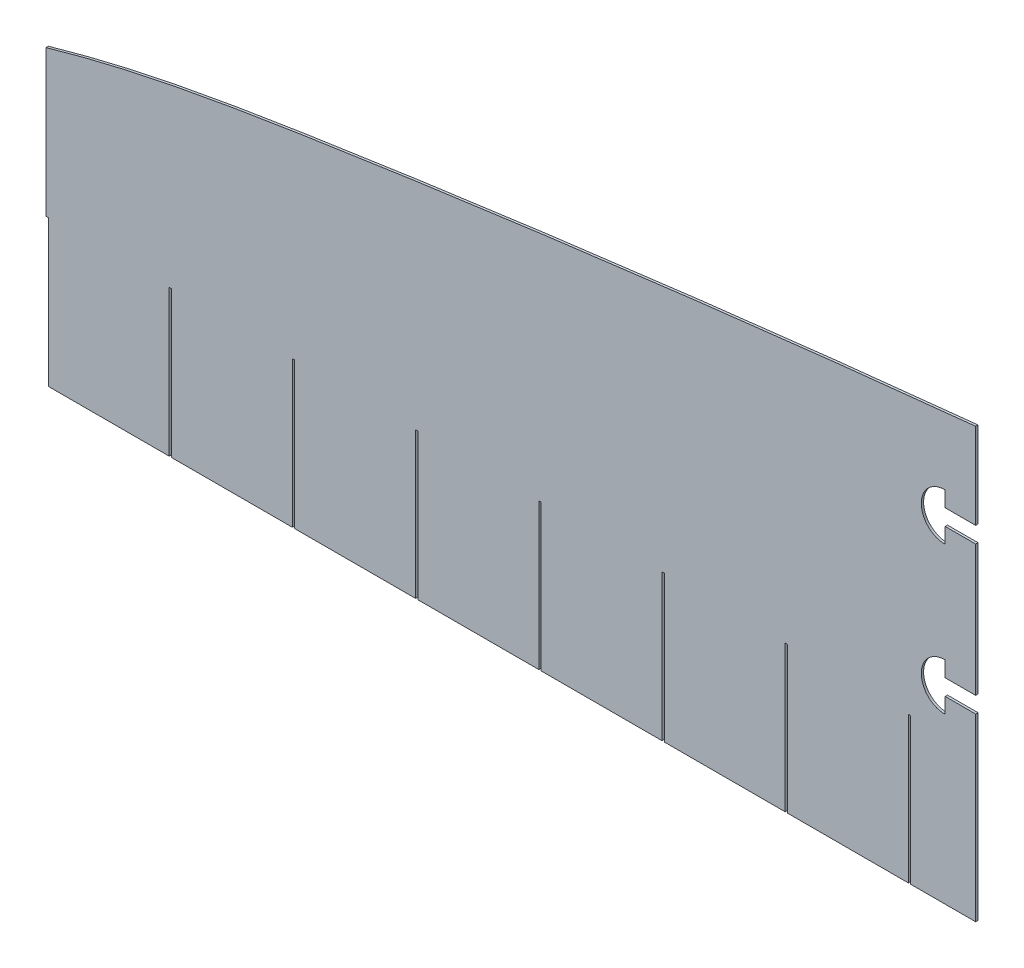
SolidWorks part; units mm, degrees
ref_plane "Front Plane" through (0, 0, 0) normal (0, 0, 1) x (1, 0, 0)
ref_plane "Top Plane" through (0, 0, 0) normal (0, 1, 0) x (1, 0, 0)
ref_plane "Right Plane" through (0, 0, 0) normal (1, 0, 0) x (0, 0, -1)
sketch "Model" plane through (0, 0, 0) normal (0, 0, 1) x (1, 0, 0)
  line L0 (1255.301, 443.0278) -> (1294.701, 443.0278)
  line L1 (1294.701, 443.0278) -> (1294.701, 553.8493)
  line L2 (94.901, 188.6103) -> (94.901, 377.2207)
  line L3 (97.901, 188.6103) -> (94.901, 188.6103)
  line L4 (97.901, 0) -> (97.901, 188.6103)
  line L5 (97.901, 0) -> (253.901, 0)
  line L6 (253.901, 188.6103) -> (253.901, 0)
  line L7 (256.901, 188.6103) -> (253.901, 188.6103)
  line L8 (256.901, 0) -> (256.901, 188.6103)
  line L9 (256.901, 0) -> (412.901, 0)
  line L10 (412.901, 188.6103) -> (412.901, 0)
  line L11 (415.901, 188.6103) -> (412.901, 188.6103)
  line L12 (415.901, 0) -> (415.901, 188.6103)
  line L13 (415.901, 0) -> (571.901, 0)
  line L14 (571.901, 188.6103) -> (571.901, 0)
  line L15 (574.901, 188.6103) -> (571.901, 188.6103)
  line L16 (574.901, 0) -> (574.901, 188.6103)
  line L17 (574.901, 0) -> (730.901, 0)
  line L18 (730.901, 188.6103) -> (730.901, 0)
  line L19 (733.901, 188.6103) -> (730.901, 188.6103)
  line L20 (733.901, 0) -> (733.901, 188.6103)
  line L21 (733.901, 0) -> (889.901, 0)
  line L22 (889.901, 188.6103) -> (889.901, 0)
  line L23 (892.901, 188.6103) -> (889.901, 188.6103)
  line L24 (892.901, 0) -> (892.901, 188.6103)
  line L25 (892.901, 0) -> (1048.901, 0)
  line L26 (1048.901, 188.6103) -> (1048.901, 0)
  line L27 (1051.901, 188.6103) -> (1048.901, 188.6103)
  line L28 (1051.901, 0) -> (1051.901, 188.6103)
  line L29 (1051.901, 0) -> (1207.901, 0)
  line L30 (1207.901, 188.6103) -> (1207.901, 0)
  line L31 (1210.901, 188.6103) -> (1207.901, 188.6103)
  line L32 (1210.901, 0) -> (1210.901, 188.6103)
  line L33 (1210.901, 0) -> (1294.701, 0)
  line L34 (1294.701, 0) -> (1294.701, 232.2278)
  line L35 (1255.301, 232.2278) -> (1294.701, 232.2278)
  line L36 (1255.301, 212.2304) -> (1255.301, 232.2278)
  line L37 (1255.301, 253.0278) -> (1255.301, 273.0252)
  line L38 (1255.301, 253.0278) -> (1294.701, 253.0278)
  line L39 (1294.701, 253.0278) -> (1294.701, 422.2278)
  line L40 (1255.301, 422.2278) -> (1294.701, 422.2278)
  line L41 (1255.301, 402.2304) -> (1255.301, 422.2278)
  line L42 (1255.301, 443.0278) -> (1255.301, 463.0252)
  arc A0 (1255.301, 273.0252) -> (1255.301, 212.2304) centre (1254.901, 242.6278) ccw
  arc A1 (1255.301, 463.0252) -> (1255.301, 402.2304) centre (1254.901, 432.6278) ccw
  spline S0 degree 3 poles (1294.701, 553.8493) (987.966, 523.1395) (557.6029, 467.7803) (240.864, 415.199) (137.9733, 389.6909) (94.901, 377.2207) knots 0.108777 0.108777 0.108777 0.108777 0.189662 0.216203 0.23816 0.23816 0.23816 0.23816
extrude "Boss-Extrude1" add sketch "Model" along normal blind 3
